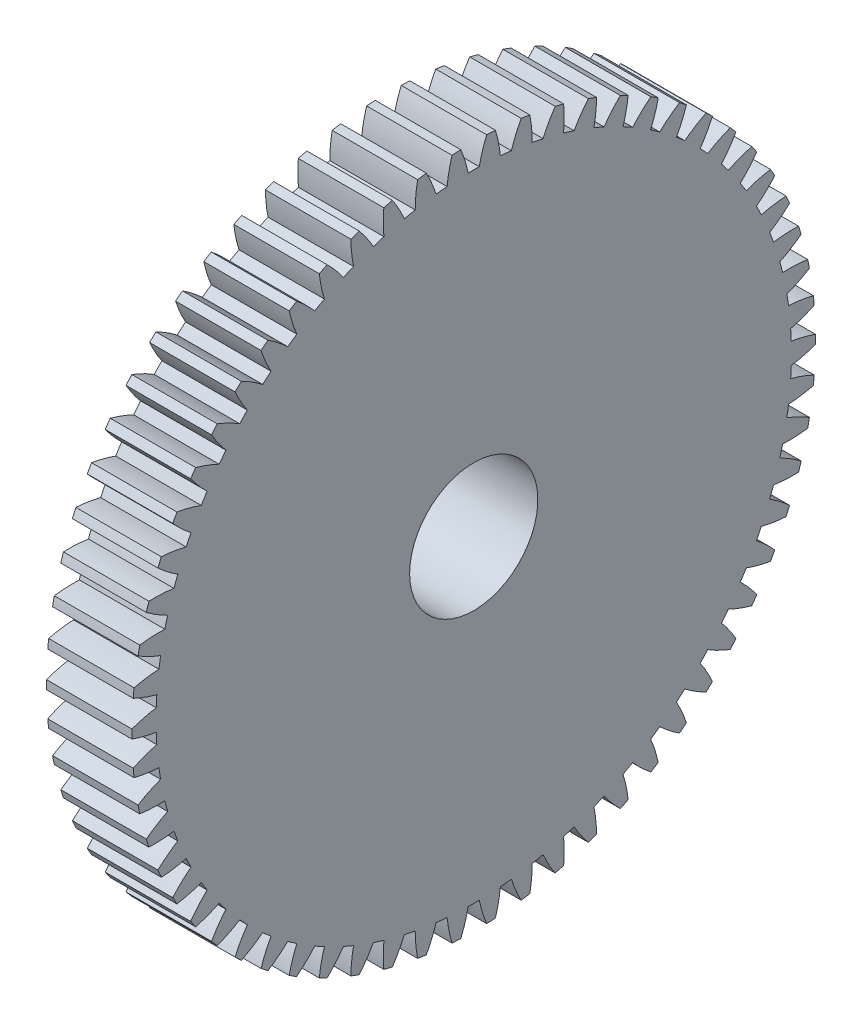
SolidWorks part; units mm, degrees
ref_plane "Plane1" through (0, 0, 0) normal (0, 0, 1) x (1, 0, 0)
ref_plane "Plane2" through (0, 0, 0) normal (0, 1, 0) x (1, 0, 0)
ref_plane "Plane3" through (0, 0, 0) normal (1, 0, 0) x (0, 0, -1)
sketch "HoldingSke" plane through (0, 0, 0) normal (0, 1, 0) x (1, 0, 0)
  line L0 (0, 0) -> (381.5865, -717.6598)
  line L1 (-15, 0) -> (100, 0) construction
  line L2 (0, 0) -> (-2.1039, 2.3779)
  line L3 (0, 0) -> (-11.863, 4.5341)
  line L4 (0, 0) -> (4.0544, 7.6251)
  line L5 (0, 0) -> (-14.8741, -5.5476)
  line L6 (0, 0) -> (-5.2639, -3.5516)
  line L7 (-2.1039, 2.3779) -> (1.3132, 17.8808)
  line L8 (-76.2, 54.61) -> (-65.4837, 54.61)
  line L9 (-67.7845, 28.3722) -> (-49.3413, 33.142)
  line L10 (-76.2, 71.12) -> (104.1128, 71.12)
  line L11 (0, 0) -> (-6.35, 0)
  line L12 (-76.2, 101.6) -> (-76.1716, 101.6)
  line L13 (24.9733, 27.94) -> (52.9518, 28.4284)
  line L14 (24.9733, 27.94) -> (25.0241, 27.9398)
  line L15 (24.9733, 27.94) -> (100.4021, 29.52)
  circle A0 centre (0, 0) radius 4.7625
  circle A1 centre (0, 0) radius 7.9375
  circle A2 centre (0, 0) radius 7.9375
  circle A3 centre (0, 0) radius 4.7625
  dimension "MHD" = 15.875
  dimension "Hub_dia" = 15.875
  dimension "Bore" = 9.525
  dimension "MBD" = 9.525
  dimension "Num_teeth" = 62
  dimension "Pitch_radius" = 180.3128
  dimension "Pitch" = 812.8
  dimension "Width" = 6.35
  dimension "Overall_len" = 15.875
  dimension "Show_teeth" = 62
  dimension "Thickness" = 6.35
  dimension "OAL" = 15.8751
  dimension "T_dim" = 10.7163
  dimension "Ap" = 14.5
  dimension "H" = 19.05
  dimension "Backlash" = 0.0284
  dimension "Addendum_fac" = 1
  dimension "Dedendum_fac" = 1.2
  dimension "Clearance_fac" = 0.2
  dimension "Dedendum_add" = 0.0508
sketch "BasProSke" plane through (0, 0, 0) normal (0, 1, 0) x (1, 0, 0)
  line L0 (-10, 0) -> (60, 0) construction
  line L1 (0, 0) -> (0, 25.4)
  line L2 (0, 0) -> (6.35, 0)
  line L3 (6.35, 0) -> (6.35, 25.4)
  line L4 (6.35, 25.4) -> (0, 25.4)
  dimension "Diameter" = 50.8
  dimension "Thickness" = 6.35
revolve "Base-Revolve" add sketch "BasProSke" angle 360 about L0
sketch "TooCutSke" plane through (0, 0, 0) normal (1, 0, 0) x (0, 0, -1)
  line L1 (0, 0) -> (0, 107) construction
  line L2 (0, 0) -> (-0.6731, 24.597) construction
  line L3 (0, 0) -> (-2.4919, 49.136) construction
  line L4 (-0.6731, 24.597) -> (-1.2459, 24.568) construction
  arc A0 (0.4109, 23.5994) -> (-0.4109, 23.5994) centre (0, 0) ccw
  arc A1 (0.9718, 25.4068) -> (-0.9718, 25.4068) centre (0, 0) ccw
  circle A2 centre (0, 0) radius 24.6062 construction
  circle A3 centre (0, 0) radius 23.8225 construction
  arc A4 (-0.4109, 23.5994) -> (-0.9718, 25.4068) centre (-10.0481, 21.5997) ccw
  arc A5 (0.9718, 25.4068) -> (0.4109, 23.5994) centre (10.0481, 21.5997) ccw
  dimension "Root_dia" = 47.2059
  dimension "Overcut_dia" = 50.8508
  dimension "Pitch_dia" = 49.2125
  dimension "Base_dia" = 47.645
  dimension "Flank_rad" = 9.8425
  dimension "Half_ang" = 2.903
  dimension "Half_CT" = 0.5736
extrude "ToothCut" cut sketch "TooCutSke" along normal through all
fillet "Breaks" [suppressed] radius 0.0159
fillet "RootFillets" [suppressed] radius 0.2095
pattern_circular "TeethCuts" count 62 every 5.806 about axis through (-10, 0, 0) along (1, 0, 0) of "ToothCut", "RootFillets", "Breaks"
sketch "HubNeaOneSke" plane through (0, 0, 0) normal (-1, 0, 0) x (0, 0, 1)
  circle A0 centre (0, 0) radius 7.9375
  dimension "Diameter" = 15.875
extrude "HubNearOne" add sketch "HubNeaOneSke" along normal blind 9.5251
sketch "HubNeaBotSke" plane through (0, 0, 0) normal (-1, 0, 0) x (0, 0, 1)
  circle A0 centre (0, 0) radius 7.9375
  dimension "Diameter" = 15.875
extrude "HubNearBoth" [suppressed] add sketch "HubNeaBotSke" along normal blind 4.7625
ref_plane "FarPln" through (6.35, 0, 0) normal (1, 0, 0) x (0, 0, -1)
sketch "HubFarSke" plane through (6.35, 0, 0) normal (1, 0, 0) x (0, 0, -1)
  circle A0 centre (0, 0) radius 7.9375
  dimension "Diameter" = 15.875
extrude "HubFar" [suppressed] add sketch "HubFarSke" along normal blind 4.7625
sketch "BorSke" plane through (0, 0, 0) normal (1, 0, 0) x (0, 0, -1)
  circle A0 centre (0, 0) radius 4.7625
  dimension "Diameter" = 9.525
extrude "Bore" cut sketch "BorSke" along normal mid plane 31.7501
sketch "KeySke" plane through (0, 0, 0) normal (1, 0, 0) x (0, 0, -1)
  line L0 (-1.1913, 0) -> (-1.1913, 5.9538)
  line L1 (-1.1913, 5.9538) -> (1.1913, 5.9538)
  line L2 (1.1913, 5.9538) -> (1.1913, 0)
  line L3 (0, 0) -> (0, 34) construction
  line L4 (-1.1913, 0) -> (1.1913, 0)
  dimension "Offset" = 5.9538
  dimension "Width" = 2.3825
extrude "Keyway" [suppressed] cut sketch "KeySke" along normal mid plane 31.7501
pattern_circular "Keyway2" [suppressed] count 2 every 90 about axis through (-10, 0, 0) along (1, 0, 0)
equation "' \"Pitch@HoldingSke\" = 4"
equation "' \"Num_teeth@HoldingSke\" = 12"
equation "' \"Ap@HoldingSke\" =  20"
equation "' \"Width@HoldingSke\" = 0.5"
equation "' \"Hub_dia@HoldingSke\"= 1"
equation "' \"Overall_len@HoldingSke\" = 1.0"
equation "' \"Bore@HoldingSke\" = 0.75"
equation "' \"T_dim@HoldingSke\" = 0.85"
equation "' \"Width@KeySke\" = 0.25"
equation "' \"Show_teeth@HoldingSke\" = 13"
equation "' \"Backlash@HoldingSke\" = 0.009"
equation "' \"Addendum_fac@HoldingSke\" = 1.0"
equation "' \"Dedendum_fac@HoldingSke\" = 1.25"
equation "' \"Dedendum_add@HoldingSke\" = 0.00005"
equation "' \"Clearance_fac@HoldingSke\" = 0.25"
equation "' \"Pitch@HoldingSke\" = 0.5"
equation "' \"Num_teeth@HoldingSke\" = 23"
equation "' \"Show_teeth@HoldingSke\" = 23"
equation "' \"Backlash@HoldingSke\" = 0.0375"
equation "\"Overcut_dia@TooCutSke\" = (\"Num_teeth@HoldingSke\" + 2 * \"Addendum_fac@HoldingSke\") / \"Pitch@HoldingSke\" + 0.002"
equation "\"Pitch_dia@TooCutSke\" = \"Num_teeth@HoldingSke\" / \"Pitch@HoldingSke\""
equation "\"Base_dia@TooCutSke\" = \"Num_teeth@HoldingSke\" / \"Pitch@HoldingSke\" * cos((\"Ap@HoldingSke\"  * 3.14159265 / 180))"
equation "\"Root_dia@TooCutSke\" = (\"Num_teeth@HoldingSke\" + 2) / \"Pitch@HoldingSke\" - 2 * (\"Addendum_fac@HoldingSke\" + \"Dedendum_fac@HoldingSke\") / \"Pitch@HoldingSke\" - \"Dedendum_add@HoldingSke\" * 2"
equation "\"Half_ang@TooCutSke\" = 180 / \"Num_teeth@HoldingSke\""
equation "\"Half_CT@TooCutSke\" = \"Num_teeth@HoldingSke\" / \"Pitch@HoldingSke\" * sin((3.14159265 / 2 / \"Num_teeth@HoldingSke\")) / 2 - 7 * \"Backlash@HoldingSke\" / 4"
equation "\"Flank_rad@TooCutSke\" = \"Num_teeth@HoldingSke\" / \"Pitch@HoldingSke\" / 5"
equation "\"Radius@RootFillets\" = \"Clearance_fac@HoldingSke\" / \"Pitch@HoldingSke\" + \"Dedendum_add@HoldingSke\""
equation "\"Break_rad@Breaks\" = 0.02 / \"Pitch@HoldingSke\""
equation "\"Thickness@HoldingSke\" = \"Width@HoldingSke\""
equation "\"OAL@HoldingSke\" = \"Thickness@HoldingSke\""
equation "\"MHD@HoldingSke\" = (\"Num_teeth@HoldingSke\" + 2) / \"Pitch@HoldingSke\" - 2 * (\"Addendum_fac@HoldingSke\" + \"Dedendum_fac@HoldingSke\")  / \"Pitch@HoldingSke\" - \"Dedendum_add@HoldingSke\" * 2"
equation "\"MBD@HoldingSke\" = (\"Num_teeth@HoldingSke\" + 2) / \"Pitch@HoldingSke\" - 2 * (\"Addendum_fac@HoldingSke\" + \"Dedendum_fac@HoldingSke\")  / \"Pitch@HoldingSke\" - \"Dedendum_add@HoldingSke\" * 2 - 0.002"
equation "\"MHD@HoldingSke\" = ((sgn( \"MHD@HoldingSke\" - \"Hub_dia@HoldingSke\" )-1)*( \"MHD@HoldingSke\" - \"Hub_dia@HoldingSke\" ))/-2+ \"Hub_dia@HoldingSke\""
equation "\"MBD@HoldingSke\" = ((sgn( \"MBD@HoldingSke\" - \"Bore@HoldingSke\" )-1)*( \"MBD@HoldingSke\" - \"Bore@HoldingSke\" ))/-2+ \"Bore@HoldingSke\""
equation "\"OAL@HoldingSke\" = ((sgn( \"OAL@HoldingSke\" - \"Overall_len@HoldingSke\" )+1)*( \"OAL@HoldingSke\" - \"Overall_len@HoldingSke\" ))/2 + \"Overall_len@HoldingSke\" + 0.000002"
equation "\"Num_teeth@TeethCuts\" = int( \"Show_teeth@HoldingSke\" ) + 1"
equation "\"Num_teeth@TeethCuts\" = ((sgn( \"Num_teeth@TeethCuts\" - \"Num_teeth@HoldingSke\" )-1)*( \"Num_teeth@TeethCuts\" - \"Num_teeth@HoldingSke\" ))/-2+ \"Num_teeth@HoldingSke\""
equation "\"Num_teeth@TeethCuts\" = ((sgn( \"Num_teeth@TeethCuts\" - 2.0)+1)*( \"Num_teeth@TeethCuts\" - 2.0))/2 +2.0"
equation "\"Angle@TeethCuts\" = 360.0 / \"Num_teeth@HoldingSke\""
equation "\"Diameter@BasProSke\" = (\"Num_teeth@HoldingSke\" + 2 * \"Addendum_fac@HoldingSke\") / \"Pitch@HoldingSke\""
equation "\"Thickness@BasProSke\"  = \"Thickness@HoldingSke\""
equation "' \"Fillet_rad@BasProSke\" =  \"Thickness@HoldingSke\" * 0.05"
equation "\"MHD@HoldingSke\" = ((sgn( \"MHD@HoldingSke\" - \"Root_dia@TooCutSke\" )-1)*( \"MHD@HoldingSke\" - \"Root_dia@TooCutSke\" ))/-2+ \"Root_dia@TooCutSke\""
equation "\"Diameter@HubNeaOneSke\" = \"MHD@HoldingSke\""
equation "\"Length@HubNearOne\" = \"OAL@HoldingSke\" - \"Thickness@BasProSke\""
equation "\"Diameter@HubNeaBotSke\" = \"MHD@HoldingSke\""
equation "\"Length@HubNearBoth\" = ( \"OAL@HoldingSke\" - \"Thickness@BasProSke\" ) / 2.0"
equation "\"Thickness@FarPln\" = \"Thickness@BasProSke\""
equation "\"Diameter@HubFarSke\" = \"MHD@HoldingSke\""
equation "\"Length@HubFar\" = ( \"OAL@HoldingSke\" - \"Thickness@BasProSke\" ) / 2.0"
equation "\"Diameter@BorSke\" = \"MBD@HoldingSke\""
equation "\"D1@Bore\" = \"OAL@HoldingSke\" * 2.0"
equation "\"D1@Keyway\" = \"OAL@HoldingSke\" * 2.0"
equation "\"Offset@KeySke\" = \"T_dim@HoldingSke\" - \"MBD@HoldingSke\" / 2.0"
